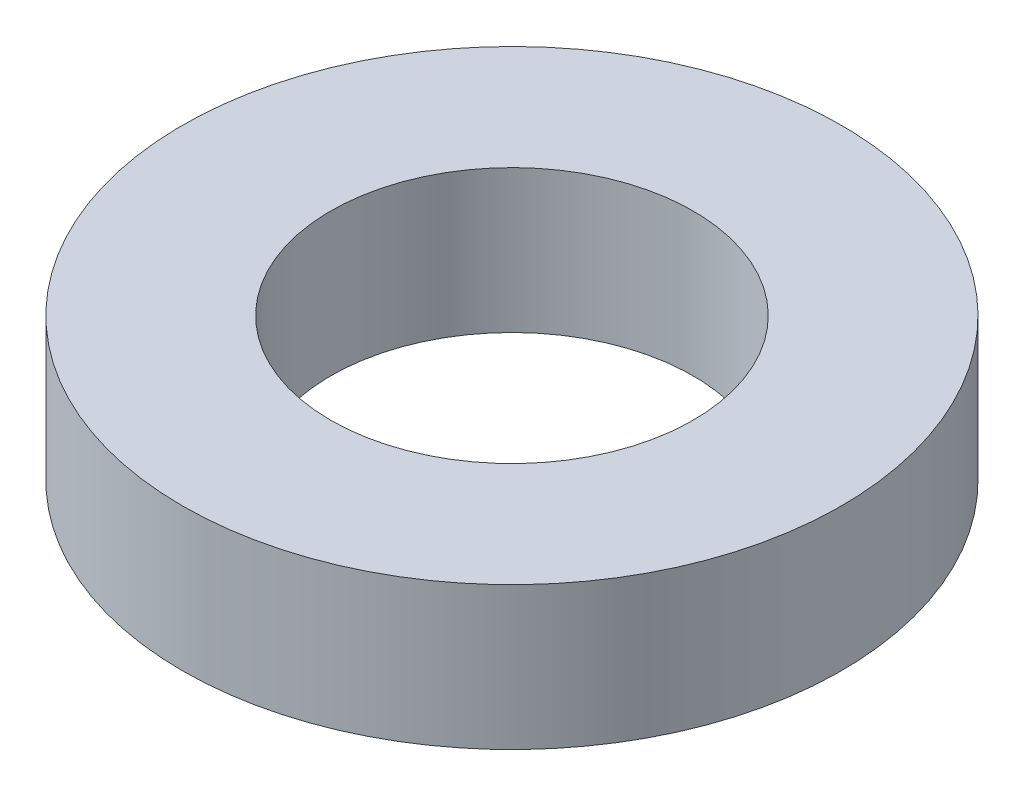
SolidWorks part; units mm, degrees
ref_plane "Front Plane" through (0, 0, 0) normal (0, 0, 1) x (1, 0, 0)
ref_plane "Top Plane" through (0, 0, 0) normal (0, 1, 0) x (1, 0, 0)
ref_plane "Right Plane" through (0, 0, 0) normal (1, 0, 0) x (0, 0, -1)
sketch "Sketch1" plane through (0, 0, 0) normal (0, 1, 0) x (1, 0, 0)
  circle A0 centre (0, 0) radius 1.65
  circle A1 centre (0, 0) radius 3
  dimension "D1" = 6
  dimension "D2" = 3.3
extrude "Boss-Extrude1" add sketch "Sketch1" along normal blind 1.3
